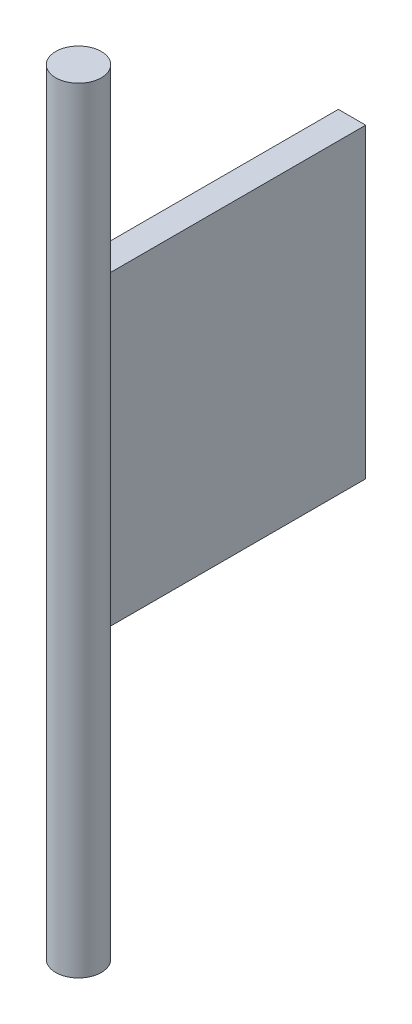
SolidWorks part; units mm, degrees
ref_plane "Alzado" through (0, 0, 0) normal (0, 0, 1) x (1, 0, 0)
ref_plane "Planta" through (0, 0, 0) normal (0, 1, 0) x (1, 0, 0)
ref_plane "Vista lateral" through (0, 0, 0) normal (1, 0, 0) x (0, 0, -1)
sketch "Croquis1" plane through (0, 0, 0) normal (1, 0, 0) x (0, 0, -1)
  line L1 (-15, 16.8) -> (15, 16.8)
  line L2 (-15, 16.8) -> (-15, -16.8)
  line L3 (-15, -16.8) -> (15, -16.8)
  line L4 (15, 16.8) -> (15, -16.8)
  line L5 (-15, 16.8) -> (15, -16.8) construction
  line L6 (-15, -16.8) -> (15, 16.8) construction
  point P0 (0, 0)
  dimension "D1" = 30
  dimension "D2" = 33.6
extrude "Saliente-Extruir1" add sketch "Croquis1" along normal blind 3
sketch "Croquis2" plane through (0, 16.8, 0) normal (0, 1, 0) x (1, 0, 0)
  line L0 (1.5, 15) -> (1.5, -15) construction
  line L1 (3, 15) -> (0, 15) construction
  line L2 (3, -15) -> (0, -15) construction
  circle A0 centre (1.5, -15) radius 2.5
  dimension "D1" = 5
extrude "Saliente-Extruir2" add sketch "Croquis2" against normal blind 65 and the other way blind 20
